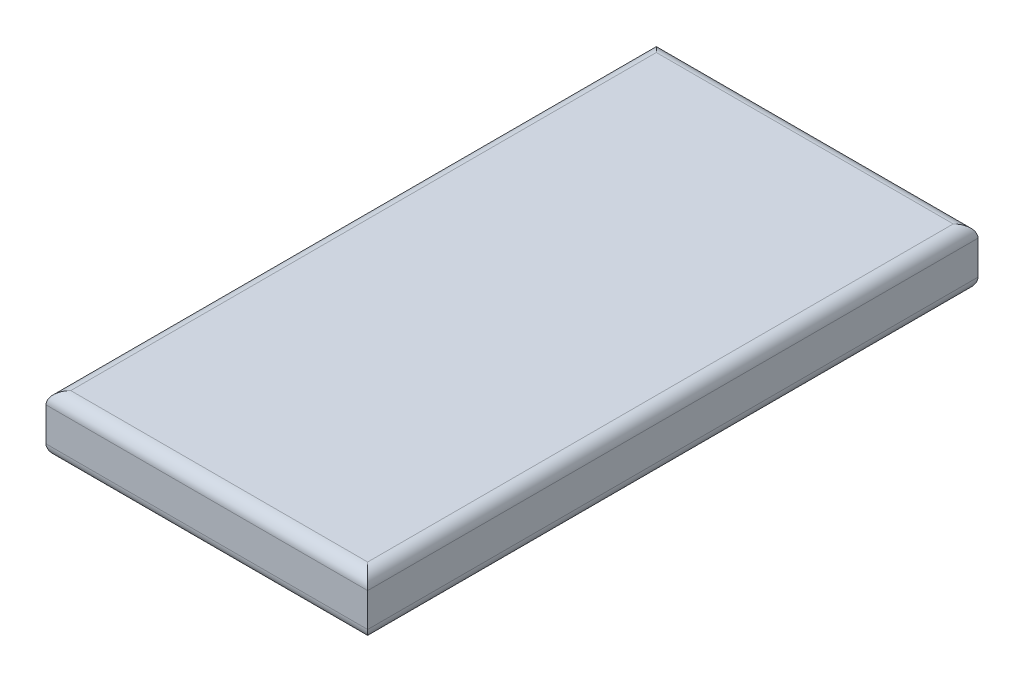
SolidWorks part; units mm, degrees
ref_plane "Front Plane" through (0, 0, 0) normal (0, 0, 1) x (1, 0, 0)
ref_plane "Top Plane" through (0, 0, 0) normal (0, 1, 0) x (1, 0, 0)
ref_plane "Right Plane" through (0, 0, 0) normal (1, 0, 0) x (0, 0, -1)
sketch "Sketch1" plane through (0, 0, 0) normal (0, 1, 0) x (1, 0, 0)
  line L1 (0, 0) -> (990.6, 0)
  line L2 (0, 0) -> (0, 1879.6)
  line L3 (0, 1879.6) -> (990.6, 1879.6)
  line L4 (990.6, 0) -> (990.6, 1879.6)
  dimension "D1" = 1879.6
  dimension "D2" = 990.6
extrude "Boss-Extrude1" add sketch "Sketch1" along normal blind 180
fillet "Fillet1" radius 38.1 8 edges at (0, 0, -939.8) (495.3, 0, -1879.6) (990.6, 0, -939.8) (495.3, 0, 0) (495.3, 180, -1879.6) (990.6, 180, -939.8) (495.3, 180, 0) (0, 180, -939.8)
